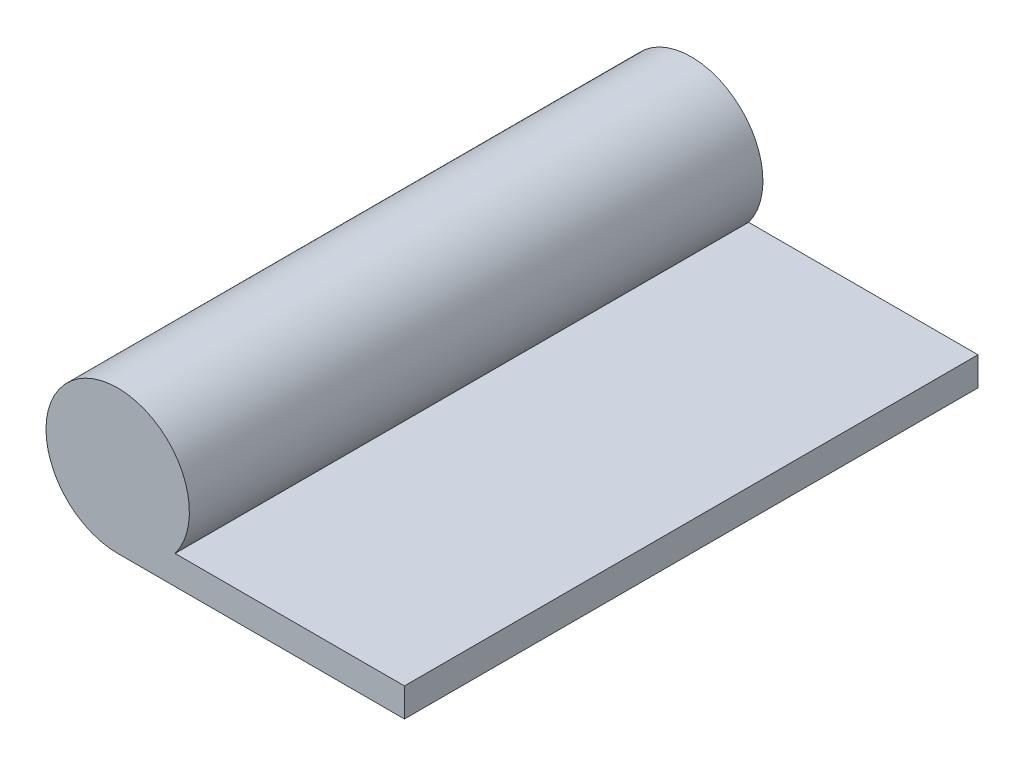
SolidWorks part; units mm, degrees
ref_plane "Front Plane" through (0, 0, 0) normal (0, 0, 1) x (1, 0, 0)
ref_plane "Top Plane" through (0, 0, 0) normal (0, 1, 0) x (1, 0, 0)
ref_plane "Right Plane" through (0, 0, 0) normal (1, 0, 0) x (0, 0, -1)
sketch "Sketch1" plane through (0, 0, 0) normal (0, 0, 1) x (1, 0, 0)
  line L1 (0, -12.5) -> (50, -12.5)
  line L3 (10, -7.5) -> (50, -7.5)
  line L4 (50, -12.5) -> (50, -7.5)
  arc A0 (10, -7.5) -> (0, -12.5) centre (0, 0) ccw
  dimension "D1" = 25
  dimension "D2" = 50
extrude "Boss-Extrude1" add sketch "Sketch1" along normal blind 100
